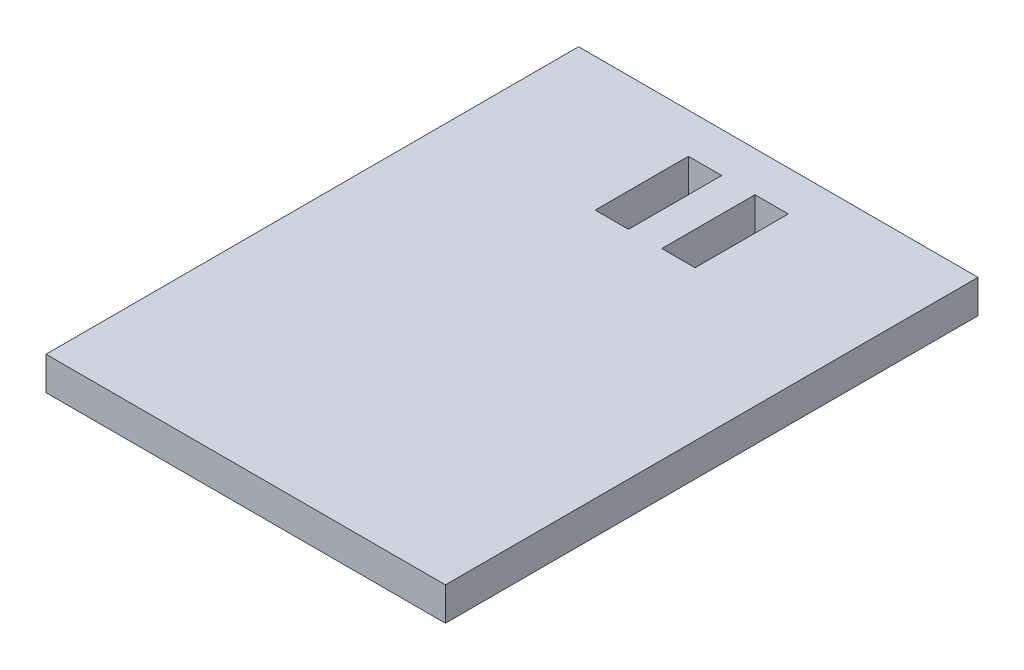
SolidWorks part; units mm, degrees
ref_plane "Front Plane" through (0, 0, 0) normal (0, 0, 1) x (1, 0, 0)
ref_plane "Top Plane" through (0, 0, 0) normal (0, 1, 0) x (1, 0, 0)
ref_plane "Right Plane" through (0, 0, 0) normal (1, 0, 0) x (0, 0, -1)
sketch "Sketch1" plane through (0, 0, 0) normal (0, 1, 0) x (1, 0, 0)
  line L1 (0, 0) -> (38.1, 0)
  line L2 (0, 0) -> (0, 50.8)
  line L3 (0, 50.8) -> (38.1, 50.8)
  line L4 (38.1, 0) -> (38.1, 50.8)
  line L5 (14.2875, 46.99) -> (17.4625, 46.99)
  line L6 (14.2875, 46.99) -> (14.2875, 38.1)
  line L7 (14.2875, 38.1) -> (17.4625, 38.1)
  line L8 (17.4625, 46.99) -> (17.4625, 38.1)
  line L9 (20.6375, 46.99) -> (23.8125, 46.99)
  line L10 (20.6375, 46.99) -> (20.6375, 38.1)
  line L11 (20.6375, 38.1) -> (23.8125, 38.1)
  line L12 (23.8125, 46.99) -> (23.8125, 38.1)
  point P9 (14.2875, 42.545)
  dimension "D1" = 38.1
  dimension "D2" = 50.8
  dimension "D3" = 8.89
  dimension "D4" = 3.175
  dimension "D5" = 14.2875
  dimension "D6" = 3.81
  dimension "D7" = 8.89
  dimension "D8" = 3.175
  dimension "D9" = 3.81
  dimension "D10" = 14.2875
extrude "Boss-Extrude1" add sketch "Sketch1" along normal blind 3.175
